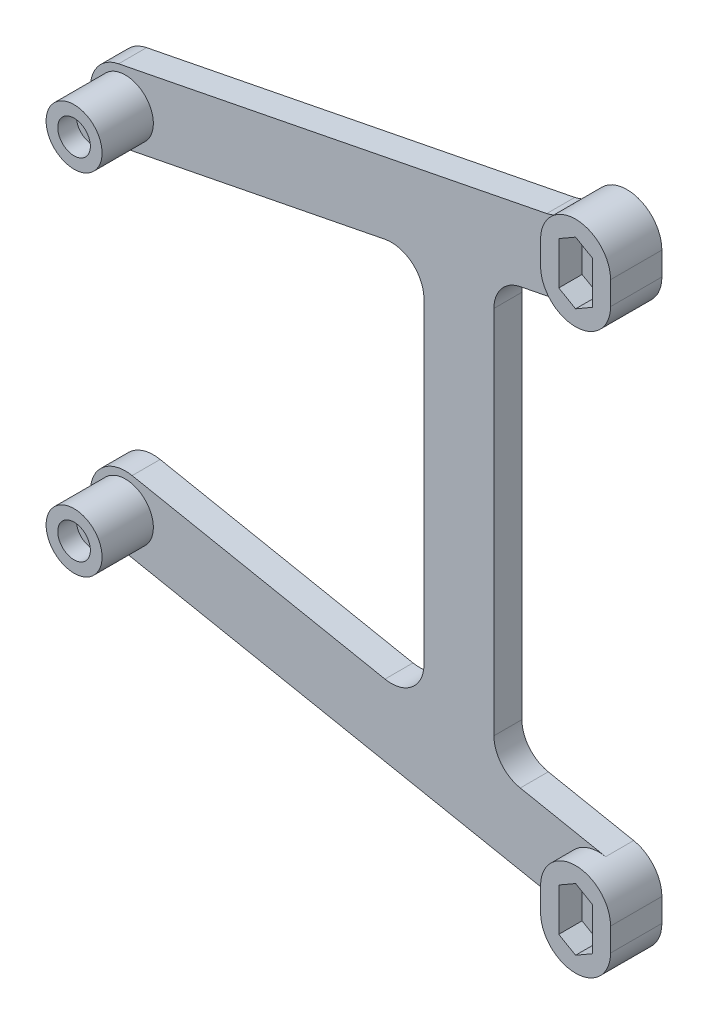
SolidWorks part; units mm, degrees
ref_plane "Front Plane" through (0, 0, 0) normal (0, 0, 1) x (1, 0, 0)
ref_plane "Top Plane" through (0, 0, 0) normal (0, 1, 0) x (1, 0, 0)
ref_plane "Right Plane" through (0, 0, 0) normal (1, 0, 0) x (0, 0, -1)
sketch "Sketch1" plane through (0, 0, 0) normal (0, 0, 1) x (1, 0, 0)
  line L58 (102.95, 87.6415) -> (84.6467, 84.0349)
  line L59 (90.3316, 100.4435) -> (-1.45, 82.3585)
  line L60 (55.6467, 78.3207) -> (1.45, 67.6415)
  line L83 (55.6467, -3.3207) -> (1.45, 7.3585)
  line L84 (79, 77.167) -> (79, -2.167)
  line L86 (64, 71.4527) -> (64, 3.5473)
  line L87 (102.6, -25) -> (102.6, -20)
  line L88 (100.4, -25) -> (100.4, -20)
  line L91 (109, 100) -> (109, 95)
  line L92 (100.4, 100) -> (100.4, 95)
  line L93 (109, -25) -> (109, -20)
  line L94 (90.3316, -25.4435) -> (-1.45, -7.3585)
  line L95 (102.6, 100) -> (102.6, 95)
  line L96 (102.95, -12.6415) -> (84.6467, -9.0349)
  circle A33 centre (0, 0) radius 4.5
  arc A42 (102.6, -25) -> (100.4, -25) centre (101.5, -25) cw
  arc A43 (100.4, -20) -> (102.6, -20) centre (101.5, -20) cw
  arc A48 (109, -20) -> (102.95, -12.6415) centre (101.5, -20) ccw
  arc A50 (95.0233, -28.7818) -> (109, -25) centre (101.5, -25) ccw
  arc A51 (1.45, 7.3585) -> (-1.45, -7.3585) centre (0, 0) ccw
  arc A52 (1.45, 67.6415) -> (-1.45, 82.3585) centre (0, 75) cw
  arc A53 (95.0233, 103.7818) -> (109, 100) centre (101.5, 100) cw
  arc A54 (109, 95) -> (102.95, 87.6415) centre (101.5, 95) cw
  arc A55 (100.4, 95) -> (102.6, 95) centre (101.5, 95) ccw
  arc A56 (102.6, 100) -> (100.4, 100) centre (101.5, 100) ccw
  circle A57 centre (0, 75) radius 4.5
  arc A58 (95.0233, -28.7818) -> (90.3316, -25.4435) centre (88.9783, -32.3115) ccw
  arc A59 (95.0233, 103.7818) -> (90.3316, 100.4435) centre (88.9783, 107.3115) cw
  arc A60 (64, 71.4527) -> (55.6467, 78.3207) centre (57, 71.4527) ccw
  arc A61 (79, 77.167) -> (84.6467, 84.0349) centre (86, 77.167) cw
  arc A62 (64, 3.5473) -> (55.6467, -3.3207) centre (57, 3.5473) cw
  arc A63 (79, -2.167) -> (84.6467, -9.0349) centre (86, -2.167) ccw
extrude "Boss-Extrude1" add sketch "Sketch1" along normal blind 6
sketch "Sketch2" plane through (0, 0, 6) normal (0, 0, 1) x (1, 0, 0)
  circle A0 centre (0, 75) radius 6
  circle A1 centre (0, 75) radius 3.5
  circle A2 centre (0, 0) radius 3.5
  circle A3 centre (0, 0) radius 6
extrude "Boss-Extrude2" add sketch "Sketch2" along normal blind 11
sketch "Sketch3" plane through (0, 0, 0) normal (0, 0, -1) x (-1, 0, 0)
  circle A0 centre (0, 75) radius 3.5
  circle A1 centre (0, 75) radius 1.65
  circle A2 centre (0, 0) radius 3.5
  circle A3 centre (0, 0) radius 1.65
extrude "Boss-Extrude3" add sketch "Sketch3" against normal offset from surface (7 mm away) 4 from offset 6 up to face at (6, 75, 17) offset against normal yes
sketch "Sketch4" plane through (0, 0, 6) normal (0, 0, 1) x (1, 0, 0)
  line L2 (94, -20) -> (94, -25)
  line L4 (109, -20) -> (109, -25)
  line L6 (94, 100) -> (94, 95)
  line L8 (109, 100) -> (109, 95)
  line L9 (101.5, -15.8431) -> (97.9, -17.9215)
  line L14 (105.1, -17.9215) -> (101.5, -15.8431)
  line L17 (97.9, -27.0785) -> (101.5, -29.1569)
  line L18 (101.5, -29.1569) -> (105.1, -27.0785)
  line L21 (101.5, 104.1569) -> (97.9, 102.0785)
  line L26 (105.1, 102.0785) -> (101.5, 104.1569)
  line L29 (97.9, 92.9215) -> (101.5, 90.8431)
  line L30 (101.5, 90.8431) -> (105.1, 92.9215)
  line L34 (97.9, 102.0785) -> (97.9, 92.9215)
  line L36 (105.1, 102.0785) -> (105.1, 92.9215)
  line L38 (97.9, -17.9215) -> (97.9, -27.0785)
  line L40 (105.1, -17.9215) -> (105.1, -27.0785)
  arc A0 (109, 100) -> (94, 100) centre (101.5, 100) ccw
  arc A1 (94, 95) -> (109, 95) centre (101.5, 95) ccw
  arc A2 (109, -20) -> (94, -20) centre (101.5, -20) ccw
  arc A3 (94, -25) -> (109, -25) centre (101.5, -25) ccw
extrude "Boss-Extrude4" add sketch "Sketch4" along normal blind 5
